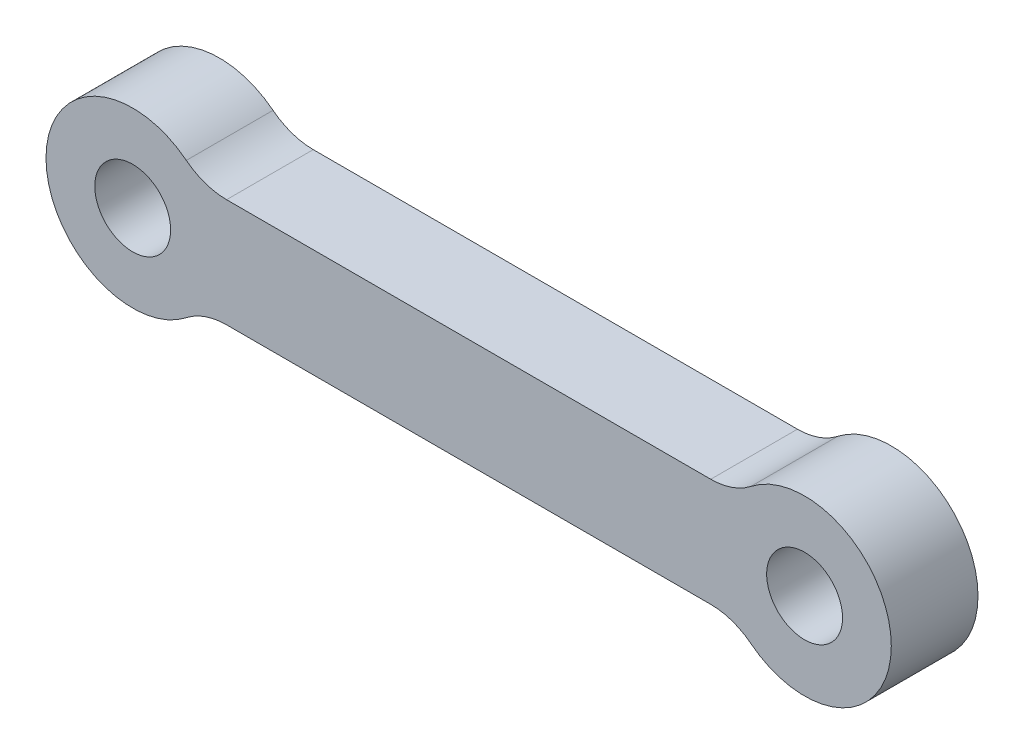
SolidWorks part; units mm, degrees
ref_plane "Front Plane" through (0, 0, 0) normal (0, 0, 1) x (1, 0, 0)
ref_plane "Top Plane" through (0, 0, 0) normal (0, 1, 0) x (1, 0, 0)
ref_plane "Right Plane" through (0, 0, 0) normal (1, 0, 0) x (0, 0, -1)
sketch "Sketch1" plane through (0, 0, 0) normal (0, 0, 1) x (1, 0, 0)
  line L0 (-15.5, 0) -> (15.5, 0) construction
  line L1 (-12.3775, 2.5) -> (12.3775, 2.5)
  line L2 (-12.3775, -2.5) -> (12.3775, -2.5)
  circle A0 centre (-15.5, 0) radius 1.75
  circle A1 centre (-15.5, 0) radius 4
  circle A2 centre (15.5, 0) radius 1.75
  circle A3 centre (15.5, 0) radius 4
  point P4 (0, 0)
  dimension "D2" = 3.5
  dimension "D3" = 8
  dimension "D1" = 31
  dimension "D4" = 2.5
extrude "Boss-Extrude1" add sketch "Sketch1" along normal mid plane 4
fillet "Fillet1" radius 3 4 edges at (-12.3775, -2.5, 0) (12.3775, -2.5, 0) (12.3775, 2.5, 0) (-12.3775, 2.5, 0)
